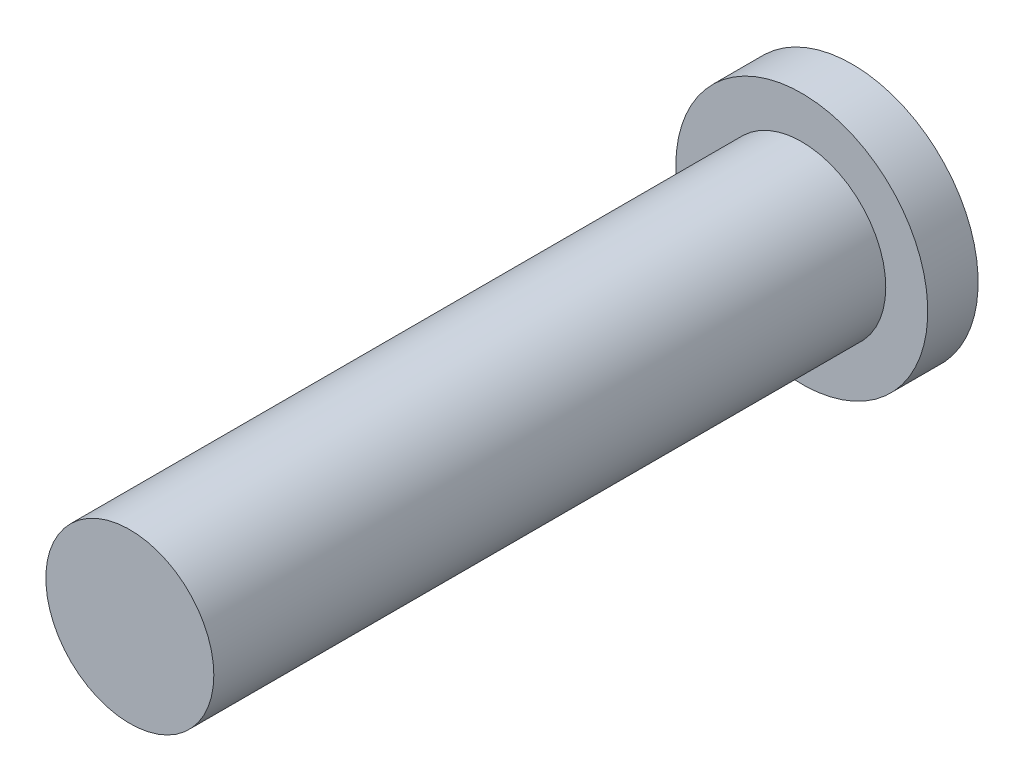
SolidWorks part; units mm, degrees
ref_plane "Alzado" through (0, 0, 0) normal (0, 0, 1) x (1, 0, 0)
ref_plane "Planta" through (0, 0, 0) normal (0, 1, 0) x (1, 0, 0)
ref_plane "Vista lateral" through (0, 0, 0) normal (1, 0, 0) x (0, 0, -1)
sketch "Croquis1" plane through (0, 0, 0) normal (0, 0, 1) x (1, 0, 0)
  circle A0 centre (0, 0) radius 5
  dimension "D1" = 10
extrude "Saliente-Extruir1" add sketch "Croquis1" along normal blind 40
sketch "Croquis2" plane through (0, 0, 0) normal (0, 0, -1) x (-1, 0, 0)
  circle A0 centre (0, 0) radius 7.5
  dimension "D1" = 15
extrude "Saliente-Extruir2" add sketch "Croquis2" along normal blind 3
